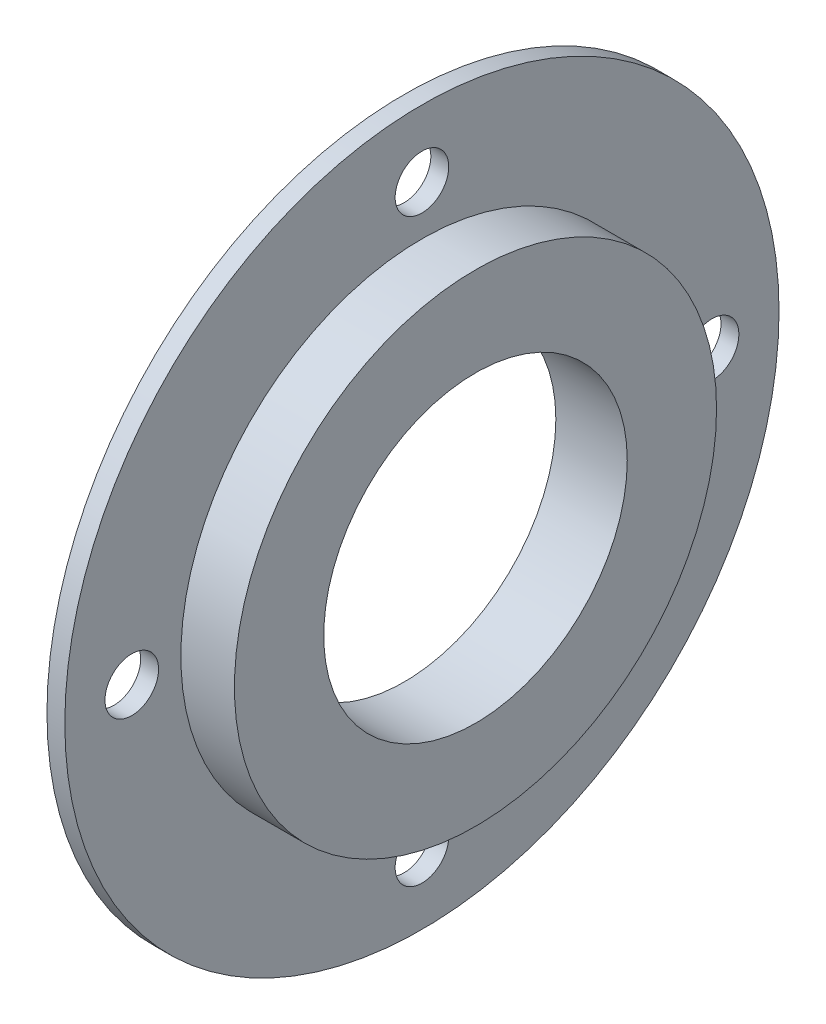
SolidWorks part; units mm, degrees
ref_plane "Front Plane" through (0, 0, 0) normal (0, 0, 1) x (1, 0, 0)
ref_plane "Top Plane" through (0, 0, 0) normal (0, 1, 0) x (1, 0, 0)
ref_plane "Right Plane" through (0, 0, 0) normal (1, 0, 0) x (0, 0, -1)
sketch "Sketch2" plane through (0, 0, 0) normal (0, 0, 1) x (1, 0, 0)
  line L0 (0, 0) -> (0, 40)
  line L1 (0, 40) -> (2, 40)
  line L2 (2, 40) -> (2, 27)
  line L3 (2, 27) -> (8, 27)
  line L4 (8, 27) -> (8, 0)
  line L5 (8, 0) -> (0, 0) construction
  line L6 (0, 0) -> (8, 0)
  dimension "D1" = 8
  dimension "D2" = 2
  dimension "D3" = 80
  dimension "D4" = 54
revolve "Revolve1" add sketch "Sketch2" angle 360 about L5
sketch "Sketch3" plane through (8, 0, 0) normal (1, 0, 0) x (0, 0, -1)
  circle A0 centre (0, 0) radius 17
  dimension "D1" = 34
extrude "Cut-Extrude1" cut sketch "Sketch3" against normal blind 10
sketch "Sketch4" plane through (8, 0, 0) normal (1, 0, 0) x (0, 0, -1)
  circle A0 centre (0, 0) radius 32.5 construction
  circle A1 centre (0, -32.5) radius 3
  circle A2 centre (32.5, 0) radius 3
  circle A3 centre (0, 32.5) radius 3
  circle A4 centre (-32.5, 0) radius 3
  dimension "D1" = 65
  dimension "D2" = 6
  dimension "D3" = 6
  dimension "D4" = 6
  dimension "D5" = 6
extrude "Cut-Extrude2" cut sketch "Sketch4" against normal blind 28
